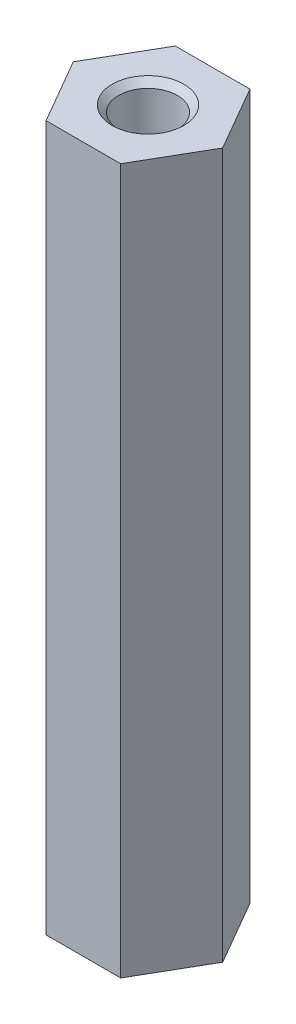
SolidWorks part; units mm, degrees
ref_plane "Front Plane" through (0, 0, 0) normal (0, 0, 1) x (1, 0, 0)
ref_plane "Top Plane" through (0, 0, 0) normal (0, 1, 0) x (1, 0, 0)
ref_plane "Right Plane" through (0, 0, 0) normal (1, 0, 0) x (0, 0, -1)
sketch "草图1" plane through (0, 0, 0) normal (0, 1, 0) x (1, 0, 0)
  line L1 (3.1754, 0) -> (1.5877, 2.75)
  line L2 (1.5877, 2.75) -> (-1.5877, 2.75)
  line L3 (-1.5877, 2.75) -> (-3.1754, 0)
  line L4 (-3.1754, 0) -> (-1.5877, -2.75)
  line L5 (-1.5877, -2.75) -> (1.5877, -2.75)
  line L6 (1.5877, -2.75) -> (3.1754, 0)
  circle A0 centre (0, 0) radius 2.75 construction
  point P1 (0, 0)
  dimension "D1" = 5.5
extrude "凸台-拉伸1" add sketch "草图1" along normal blind 30
sketch "草图4" plane through (0, 30, 0) normal (0, 1, 0) x (1, 0, 0)
  point P0 (0, 0)
hole_wizard "M3 Tapped Hole1" positions "草图4" profile "草图3" tap size "M3" standard "ISO"
sketch "草图3" plane through (0, 30, 0) normal (1, 0, 0) x (0, 0, 1)
  line L0 (0, 0) -> (0, 10.7511)
  line L1 (0, 10.7511) -> (1.25, 10)
  line L2 (1.25, 10) -> (1.25, 0.275)
  line L3 (1.25, 0.275) -> (1.525, 0)
  line L5 (1.525, 0) -> (0, 0)
  line L6 (-1.25, 0.275) -> (-1.525, 0) construction
  line L10 (0, 10.7511) -> (-1.25, 10) construction
  line L11 (0, -6.35) -> (0, 107.95) construction
  dimension "Tap Drill Dia." = 2.5
  dimension "Tap Drill Depth" = 10
  dimension "Near C'Sink Dia." = 3.05
  dimension "Near C'Sink Angle" = 90
  dimension "Drill Angle" = 118
cosmetic thread "孔螺纹线1" parameters "D1"=8, "D2"=3
sketch "草图7" plane through (0, 0, 0) normal (0, -1, 0) x (-1, 0, 0)
  point P0 (0, 0)
hole_wizard "M3 Tapped Hole2" positions "草图7" profile "草图6" tap size "M3" standard "ISO"
sketch "草图6" plane through (0, 0, 0) normal (1, 0, 0) x (0, 0, -1)
  line L0 (0, 0) -> (0, 10.7511)
  line L1 (0, 10.7511) -> (1.25, 10)
  line L2 (1.25, 10) -> (1.25, 0.275)
  line L3 (1.25, 0.275) -> (1.525, 0)
  line L5 (1.525, 0) -> (0, 0)
  line L6 (-1.25, 0.275) -> (-1.525, 0) construction
  line L10 (0, 10.7511) -> (-1.25, 10) construction
  line L11 (0, -6.35) -> (0, 107.95) construction
  dimension "Tap Drill Dia." = 2.5
  dimension "Tap Drill Depth" = 10
  dimension "Near C'Sink Dia." = 3.05
  dimension "Near C'Sink Angle" = 90
  dimension "Drill Angle" = 118
cosmetic thread "孔螺纹线2" parameters "D1"=8, "D2"=3
